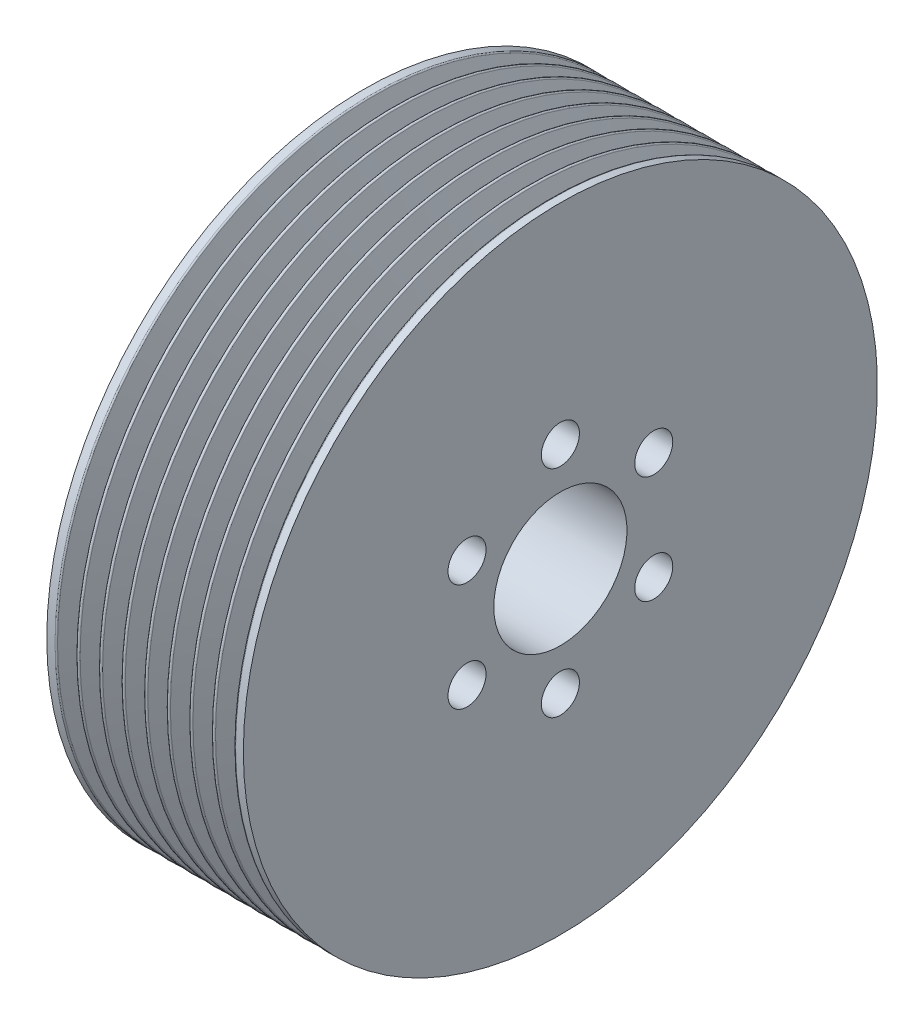
SolidWorks part; units mm, degrees
material "2018 Alloy"
ref_plane "Front Plane" through (0, 0, 0) normal (0, 0, 1) x (1, 0, 0)
ref_plane "Top Plane" through (0, 0, 0) normal (0, 1, 0) x (1, 0, 0)
ref_plane "Right Plane" through (0, 0, 0) normal (1, 0, 0) x (0, 0, -1)
sketch "Sketch1" plane through (0, 0, 0) normal (0, 0, 1) x (1, 0, 0)
  line L0 (49, 10.5) -> (49, 0) construction
  line L1 (49, 10.5) -> (49, 50)
  line L2 (49, 50) -> (18, 50)
  line L3 (18, 50) -> (18, 21.5)
  line L4 (49, 10.5) -> (31.5, 10.5)
  line L5 (0, 0) -> (49, 0) construction
  line L6 (18, 21.5) -> (31.5, 21.5)
  line L8 (0, 8.3175) -> (0, 0) construction
  line L9 (31.5, 10.5) -> (31.5, 21.5)
  dimension "D1" = 31
  dimension "D2" = 100
  dimension "D3" = 31.5
  dimension "D4" = 43
  dimension "D5" = 49
  dimension "D8" = 21
revolve "Revolve1" add sketch "Sketch1" angle 360 about L5
sketch "Sketch2" plane through (0, 0, 0) normal (0, 0, 1) x (1, 0, 0)
  line L0 (47.5451, 49.8355) -> (46.2819, 46.365)
  line L1 (45.7181, 46.365) -> (44.4549, 49.8355)
  line L2 (47.5451, 49.8355) -> (47.6049, 50) construction
  line L3 (49, 50) -> (18, 50) construction
  line L4 (44.4549, 49.8355) -> (44.3951, 50) construction
  line L5 (49, -50) -> (49, 50) construction
  line L6 (47.78, 50) -> (44.22, 50)
  line L7 (0, 0) -> (49, 0) construction
  arc A0 (47.5451, 49.8355) -> (47.78, 50) centre (47.78, 49.75) cw
  arc A1 (44.4549, 49.8355) -> (44.22, 50) centre (44.22, 49.75) ccw
  arc A2 (46.2819, 46.365) -> (45.7181, 46.365) centre (46, 46.4676) cw
  dimension "D2" = 0.25
  dimension "D3" = 0.3
  dimension "D1" = 40
  dimension "D4" = 3.56
  dimension "D5" = 3
revolve "Cut-Revolve1" cut sketch "Sketch2" angle 360 about L7
pattern_linear "LPattern1" count 8 spacing 3.56 along (-1, 0, 0) of "Cut-Revolve1"
sketch "Sketch3" plane through (49, 0, 0) normal (1, 0, 0) x (0, 0, -1)
  circle A0 centre (0, 0) radius 17 construction
  circle A1 centre (0, 17) radius 3
  circle A2 centre (14.7224, 8.5) radius 3
  circle A3 centre (14.7224, -8.5) radius 3
  circle A4 centre (0, -17) radius 3
  circle A5 centre (-14.7224, -8.5) radius 3
  circle A6 centre (-14.7224, 8.5) radius 3
  dimension "D1" = 34
  dimension "D2" = 6
  dimension "D3" = 6
extrude "Cut-Extrude1" cut sketch "Sketch3" against normal up to surface (17.5 mm away) up to face at (31.5, 0, 10.5)
